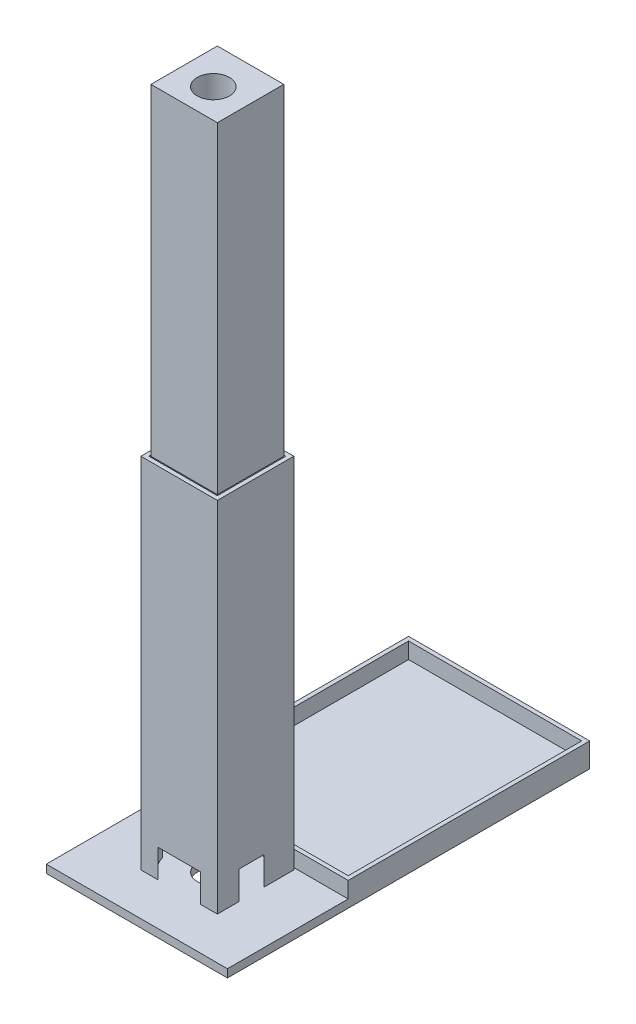
SolidWorks part; units mm, degrees
ref_plane "Front Plane" through (0, 0, 0) normal (0, 0, 1) x (1, 0, 0)
ref_plane "Top Plane" through (0, 0, 0) normal (0, 1, 0) x (1, 0, 0)
ref_plane "Right Plane" through (0, 0, 0) normal (1, 0, 0) x (0, 0, -1)
sketch "Sketch1" plane through (0, 0, 0) normal (0, 1, 0) x (1, 0, 0)
  line L0 (0, 0) -> (0, 10) construction
  line L1 (-10, -10) -> (10, -10)
  line L2 (-10, -10) -> (-10, 10)
  line L3 (-10, 10) -> (10, 10)
  line L4 (10, -10) -> (10, 10)
  line L5 (-10, -10) -> (10, 10) construction
  line L6 (-10, 10) -> (10, -10) construction
  line L7 (0, 10) -> (22.5, 10) construction
  line L8 (22.5, 10) -> (-22.5, 10)
  line L9 (-22.5, 10) -> (-22.5, 70)
  line L10 (-22.5, 70) -> (22.5, 70)
  line L11 (22.5, 70) -> (22.5, 10)
  line L12 (-22.5, 10) -> (-10, -10)
  line L13 (22.5, 10) -> (10, -10) construction
  line L14 (10, -10) -> (22.5, 10)
  line L15 (-10, -10) -> (10, -10)
  line L16 (-10, -10) -> (-10, -20)
  line L17 (-10, -20) -> (10, -20)
  line L18 (10, -10) -> (10, -20)
  circle A0 centre (0, 0) radius 4
extrude "Boss-Extrude2" add sketch "Sketch1" along normal blind 2 contours L11 L10 L9 L8 L3 | L8 L12 L2 | L4 L14 L8 | L1 L4 L3 L2 A0 | A0 | L18 L1 L16 L17
sketch "Sketch2" plane through (0, 2, 0) normal (0, 1, 0) x (1, 0, 0)
  line L0 (-21.5, 69) -> (-21.5, 11)
  line L1 (-22.5, 70) -> (22.5, 70)
  line L2 (-22.5, 70) -> (-22.5, 10)
  line L3 (-22.5, 10) -> (22.5, 10)
  line L4 (22.5, 70) -> (22.5, 10)
  line L5 (-21.5, 11) -> (21.5, 11)
  line L6 (21.5, 69) -> (21.5, 11)
  line L7 (-21.5, 69) -> (21.5, 69)
  dimension "D1" = 1
extrude "Boss-Extrude3" add sketch "Sketch2" along normal blind 4
sketch "Sketch6" plane through (0, 2, 0) normal (0, 1, 0) x (1, 0, 0)
  line L0 (-10, -20) -> (-24.7467, -20) construction
  line L1 (-22.5, 10) -> (-22.5, -20) construction
  line L2 (22.5, 10) -> (22.5, -20) construction
  line L3 (22.5, -20) -> (10, -20) construction
  line L5 (-22.5, 10) -> (22.5, 10)
  line L6 (-22.5, 10) -> (-22.5, -20)
  line L7 (-22.5, -20) -> (22.5, -20)
  line L8 (22.5, 10) -> (22.5, -20)
extrude "Boss-Extrude4" add sketch "Sketch6" against normal up to surface (2 mm away) up to face at (0, 0, -12.5)
sketch "Sketch7" plane through (0, 2, 0) normal (0, 1, 0) x (1, 0, 0)
  line L1 (0, 0) -> (0, -2) construction
  line L3 (-9.5, 9.5) -> (9.5, 9.5)
  line L4 (-9.5, 9.5) -> (-9.5, -9.5)
  line L5 (-9.5, -9.5) -> (9.5, -9.5)
  line L6 (9.5, 9.5) -> (9.5, -9.5)
  line L7 (-9.5, 9.5) -> (9.5, -9.5) construction
  line L8 (-9.5, -9.5) -> (9.5, 9.5) construction
  circle A0 centre (0, -1) radius 10
extrude "Cut-Extrude4" cut sketch "Sketch7" against normal blind 4 contours A0 L6 L3 L4 | A0 L4 L5 | A0 L5 L6
sketch "Sketch8" plane through (0, 2, 0) normal (0, 1, 0) x (1, 0, 0)
  line L53 (9.5, 2.1225) -> (9.5, 9.5)
  line L54 (9.5, 9.5) -> (-9.5, 9.5)
  line L55 (-9.5, 9.5) -> (-9.5, 2.1225)
  line L56 (9.5, 2.1225) -> (9.5, 9.5)
  line L57 (9.5, 9.5) -> (-9.5, 9.5)
  line L58 (-9.5, 9.5) -> (-9.5, 2.1225)
  line L60 (-9.5, -9.5) -> (-5.2678, -9.5)
  line L61 (-9.5, -4.1225) -> (-9.5, -9.5)
  line L62 (-9.5, -9.5) -> (-5.2678, -9.5)
  line L63 (-9.5, -4.1225) -> (-9.5, -9.5)
  line L66 (9.5, -9.5) -> (9.5, -4.1225)
  line L67 (5.2678, -9.5) -> (9.5, -9.5)
  line L68 (9.5, -9.5) -> (9.5, -4.1225)
  line L69 (5.2678, -9.5) -> (9.5, -9.5)
  arc A20 (9.5, 2.1225) -> (-9.5, 2.1225) centre (0, -1) ccw
  arc A21 (9.5, 2.1225) -> (-9.5, 2.1225) centre (0, -1) ccw
  arc A23 (-9.5, -4.1225) -> (-5.2678, -9.5) centre (0, -1) ccw
  arc A24 (-9.5, -4.1225) -> (-5.2678, -9.5) centre (0, -1) ccw
  arc A26 (5.2678, -9.5) -> (9.5, -4.1225) centre (0, -1) ccw
  arc A27 (5.2678, -9.5) -> (9.5, -4.1225) centre (0, -1) ccw
  dimension "D1" = 0
  dimension "D2" = 0
  dimension "D3" = 0
extrude "Boss-Extrude5" add sketch "Sketch8" along normal blind 7 separate body
sketch "Sketch11" plane through (0, 9, 0) normal (0, 1, 0) x (1, 0, 0)
  line L1 (-9.5, 9.5) -> (9.5, 9.5)
  line L2 (-9.5, 9.5) -> (-9.5, -9.5)
  line L3 (-9.5, -9.5) -> (9.5, -9.5)
  line L4 (9.5, 9.5) -> (9.5, -9.5)
extrude "Boss-Extrude6" add sketch "Sketch11" along normal blind 2
sketch "Sketch13" plane through (0, 11, 0) normal (0, 1, 0) x (1, 0, 0)
  line L8 (-9.5, 9.5) -> (-9.5, -9.5)
  line L9 (-9.5, -9.5) -> (9.5, -9.5)
  line L10 (9.5, -9.5) -> (9.5, 9.5)
  line L11 (9.5, 9.5) -> (-9.5, 9.5)
  line L12 (-9.5, 9.5) -> (-9.5, -9.5)
  line L13 (-9.5, -9.5) -> (9.5, -9.5)
  line L14 (9.5, -9.5) -> (9.5, 9.5)
  line L15 (9.5, 9.5) -> (-9.5, 9.5)
  dimension "D1" = 0
sketch "Sketch14" plane through (0, 0, 0) normal (0, -1, 0) x (1, 0, 0)
  line L0 (0, 0) -> (0, 1) construction
  circle A1 centre (0, 1) radius 4
extrude "Cut-Extrude7" cut sketch "Sketch14" against normal blind 19
sketch "Sketch15" plane through (0, 11, 0) normal (0, 1, 0) x (1, 0, 0)
  line L0 (9.5, 8.5) -> (-8.5, 8.5)
  line L1 (-8.5, 8.5) -> (-8.5, -8.5)
  line L2 (-8.5, -8.5) -> (9.5, -8.5)
  line L3 (8.5, -9.5) -> (8.5, 9.5)
  line L4 (0, 0) -> (9.5, 0) construction
  line L5 (9.5, 0) -> (-9.5, 0) construction
  line L6 (0, 0) -> (0, -8) construction
  line L7 (9.5, -9.5) -> (9.5, 9.5)
  line L8 (-9.5, 9.5) -> (-9.5, -9.5)
  line L9 (-9.5, -9.5) -> (9.5, -9.5)
  line L10 (9.5, -9.5) -> (9.5, 9.5)
  line L11 (9.5, 9.5) -> (-9.5, 9.5)
  line L12 (-9.5, 9.5) -> (-9.5, -9.5)
  line L13 (-9.5, -9.5) -> (9.5, -9.5)
  line L14 (9.5, -9.5) -> (9.5, 9.5)
  line L15 (9.5, 9.5) -> (-9.5, 9.5)
  line L16 (0, -8) -> (6.9282, -4)
  line L17 (6.9282, -4) -> (6.9282, 4)
  line L18 (6.9282, 4) -> (0, 8)
  line L19 (0, 8) -> (-6.9282, 4)
  line L20 (-6.9282, 4) -> (-6.9282, -4)
  line L21 (-6.9282, -4) -> (0, -8)
  line L22 (9.5, 9.5) -> (-9.5, 9.5)
  line L23 (-9.5, 9.5) -> (-9.5, -9.5)
  circle A0 centre (0, 0) radius 6.9282 construction
  line M17 (-9.5, 9.5) -> (-9.5, -9.5)
  line M18 (-9.5, -9.5) -> (9.5, -9.5)
  line M19 (9.5, -9.5) -> (9.5, 9.5)
  line M20 (9.5, 9.5) -> (-9.5, 9.5)
  dimension "D2" = 0
  dimension "D1" = 0
  dimension "D3" = 1
extrude "Boss-Extrude7" add sketch "Sketch15" along normal blind 80 contours L3 L2 L1 L0 M18 M20 M17 | L3 L2 L0 M19 | L3 L0 M19 M20 | L3 L2 M18 M19
sketch "Sketch16" plane through (0, 91, 0) normal (0, 1, 0) x (1, 0, 0)
  line L8 (-8.5, -8.5) -> (8.5, -8.5)
  line L9 (8.5, -8.5) -> (8.5, 8.5)
  line L10 (8.5, 8.5) -> (-8.5, 8.5)
  line L11 (-8.5, 8.5) -> (-8.5, -8.5)
  line L12 (-8.5, -8.5) -> (8.5, -8.5)
  line L13 (8.5, -8.5) -> (8.5, 8.5)
  line L14 (8.5, 8.5) -> (-8.5, 8.5)
  line L15 (-8.5, 8.5) -> (-8.5, -8.5)
  line L20 (-8.25, -8.25) -> (8.25, -8.25)
  line L21 (8.25, -8.25) -> (8.25, 8.25)
  line L22 (8.25, 8.25) -> (-8.25, 8.25)
  line L23 (-8.25, 8.25) -> (-8.25, -8.25)
  line L24 (-8.25, -8.25) -> (8.25, -8.25)
  line L25 (8.25, -8.25) -> (8.25, 8.25)
  line L26 (8.25, 8.25) -> (-8.25, 8.25)
  line L27 (-8.25, 8.25) -> (-8.25, -8.25)
  dimension "D1" = 1
  dimension "D2" = 1.25
extrude "Boss-Extrude8" add sketch "Sketch16" along normal blind 80 separate body contours L24 L25 L26 L27
sketch "Sketch17" plane through (0, 0, 0) normal (0, -1, 0) x (1, 0, 0)
  circle A2 centre (0, 1) radius 4
  circle A3 centre (0, 1) radius 4
  dimension "D1" = 0
extrude "Cut-Extrude8" cut sketch "Sketch17" against normal blind 193
